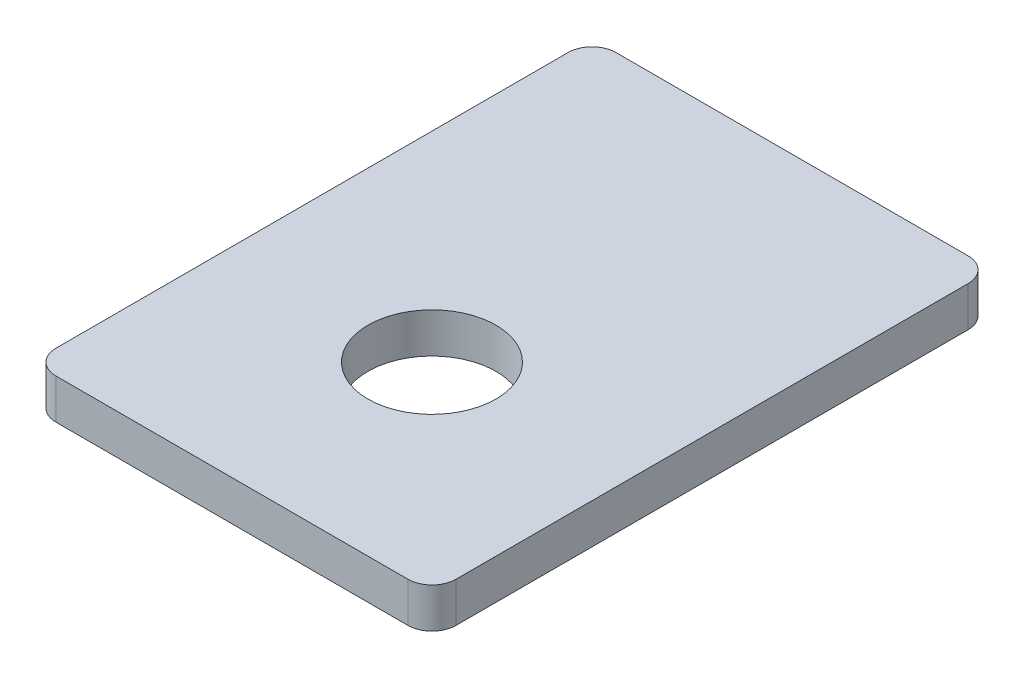
SolidWorks part; units mm, degrees
ref_plane "前视基准面" through (0, 0, 0) normal (0, 0, 1) x (1, 0, 0)
ref_plane "上视基准面" through (0, 0, 0) normal (0, 1, 0) x (1, 0, 0)
ref_plane "右视基准面" through (0, 0, 0) normal (1, 0, 0) x (0, 0, -1)
other "Configuration Table"
sketch "草图1" plane through (0, 0, 0) normal (0, 0, 1) x (1, 0, 0)
  line L0 (0, 0) -> (50, 0)
  line L1 (50, 0) -> (50, 5)
  line L2 (50, 5) -> (0, 5)
  line L3 (0, 5) -> (0, 0)
  dimension "width" = 50
  dimension "height" = 5
extrude "BlockExtrude" add sketch "草图1" along normal blind 70
fillet "Fillet" radius 3 4 edges at (0, 2.5, 0) (50, 2.5, 0) (0, 2.5, 70) (50, 2.5, 70)
sketch "草图2" plane through (0, 5, 0) normal (0, 1, 0) x (1, 0, 0)
  circle A0 centre (25, -45) radius 8
  dimension "diameter" = 16
  dimension "x" = 25
  dimension "y" = 45
extrude "Rotary_seal_seat" cut sketch "草图2" against normal through all
